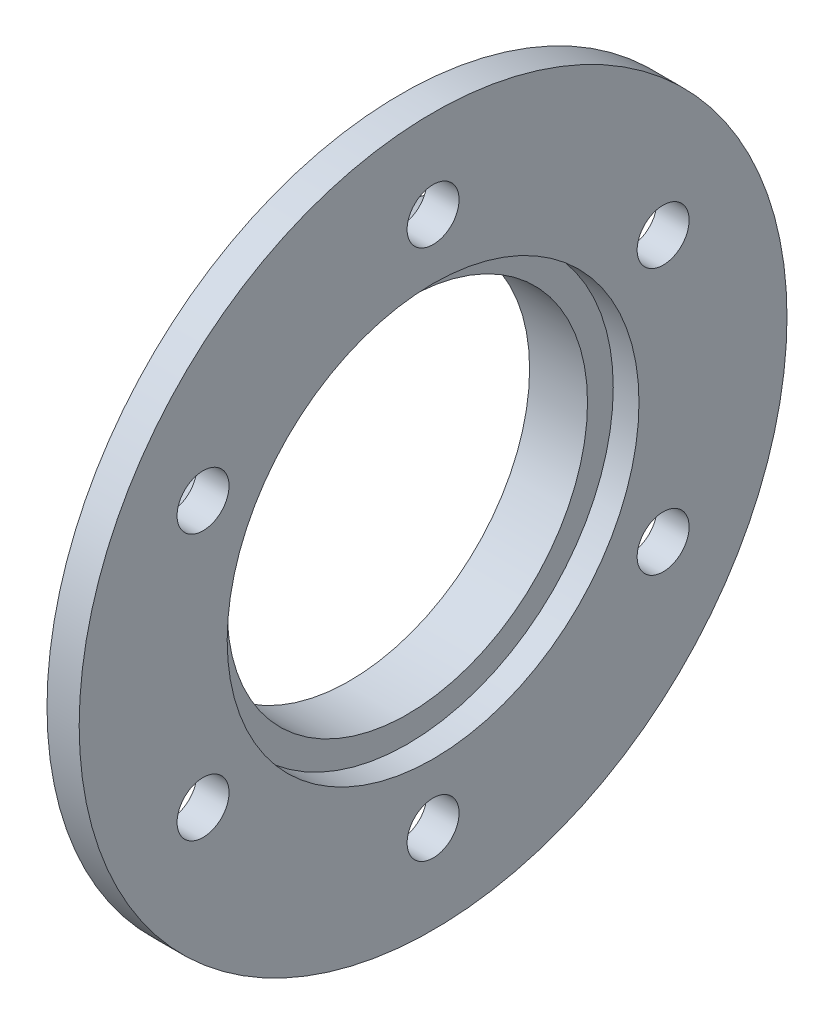
SolidWorks part; units mm, degrees
material "6061-T6 (SS)"
ref_plane "Front Plane" through (0, 0, 0) normal (0, 0, 1) x (1, 0, 0)
ref_plane "Top Plane" through (0, 0, 0) normal (0, 1, 0) x (1, 0, 0)
ref_plane "Right Plane" through (0, 0, 0) normal (1, 0, 0) x (0, 0, -1)
sketch "Sketch1" plane through (0, 0, 0) normal (1, 0, 0) x (0, 0, -1)
  line L0 (0, 0) -> (0, 20.64) construction
  arc A0 (-1.6237, 23.2194) -> (1.6237, -23.2194) centre (0, 0) ccw construction
  arc A1 (1.0588, 18.9205) -> (-1.0588, 22.3595) centre (0, 20.64) ccw construction
  circle A2 centre (0, 0) radius 27.5
  circle A3 centre (0, 20.64) radius 2.0193
  circle A4 centre (17.8748, 10.32) radius 2.0193
  circle A5 centre (17.8748, -10.32) radius 2.0193
  circle A6 centre (0, -20.64) radius 2.0193
  circle A7 centre (-17.8748, -10.32) radius 2.0193
  circle A8 centre (-17.8748, 10.32) radius 2.0193
  circle A9 centre (0, 0) radius 17.46 construction
  point P21 (0, 0)
  dimension "D1" = 23.2761
  dimension "D2" = 2.0193
  dimension "D3" = 20.64
  dimension "D5" = 34.92
  dimension "D6" = 55
  dimension "D4" = 6
extrude "Boss-Extrude1" add sketch "Sketch1" along normal blind 2.5
sketch "Sketch2" plane through (0, 0, 0) normal (-1, 0, 0) x (0, 0, 1)
  circle A0 centre (0, 0) radius 17.46 construction
  circle A1 centre (0, 0) radius 17.46
extrude "Boss-Extrude2" add sketch "Sketch2" along normal blind 4
chamfer "Chamfer5" distance 1 angle 45 1 edges at (-4, 0, 17.46)
sketch "Sketch6" plane through (-4, 0, 0) normal (1, 0, 0) x (0, 0, -1)
  line L0 (0, 14) -> (0, -14) construction
  circle A1 centre (0, 0) radius 14
  point P3 (0, 14)
  point P4 (0, -14)
  dimension "D1" = 28
extrude "Cut-Extrude1" cut sketch "Sketch6" along normal blind 10
sketch "Sketch9" plane through (2.5, 0, 0) normal (1, 0, 0) x (0, 0, -1)
  circle A0 centre (0, 0) radius 16
  dimension "D1" = 32
extrude "Cut-Extrude2" cut sketch "Sketch9" against normal blind 2
